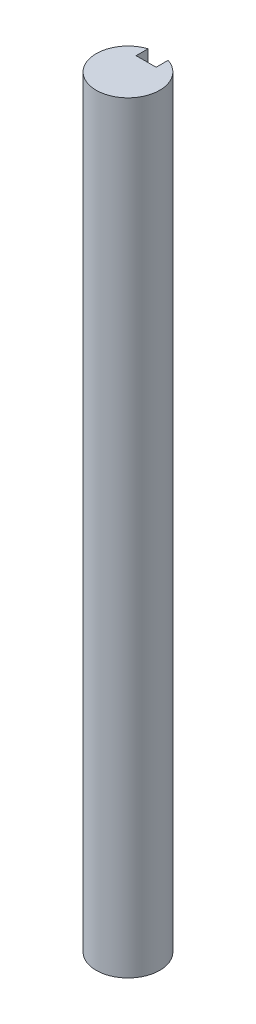
SolidWorks part; units mm, degrees
material "1023 Carbon Steel Sheet (SS)"
ref_plane "Front Plane" through (0, 0, 0) normal (0, 0, 1) x (1, 0, 0)
ref_plane "Top Plane" through (0, 0, 0) normal (0, 1, 0) x (1, 0, 0)
ref_plane "Right Plane" through (0, 0, 0) normal (1, 0, 0) x (0, 0, -1)
sketch "Sketch1" plane through (0, 0, 0) normal (0, 1, 0) x (1, 0, 0)
  line L0 (-1, 3.0134) -> (-1, 1.8134)
  line L1 (-1, 1.8134) -> (1, 1.8134)
  line L2 (1, 1.8134) -> (1, 3.0134)
  arc A0 (-1, 3.0134) -> (1, 3.0134) centre (0, 0) ccw
  point P5 (0, 1.8134)
  dimension "D1" = 6.35
  dimension "D2" = 2
  dimension "D3" = 1.2
extrude "Boss-Extrude1" add sketch "Sketch1" along normal blind 76.2
